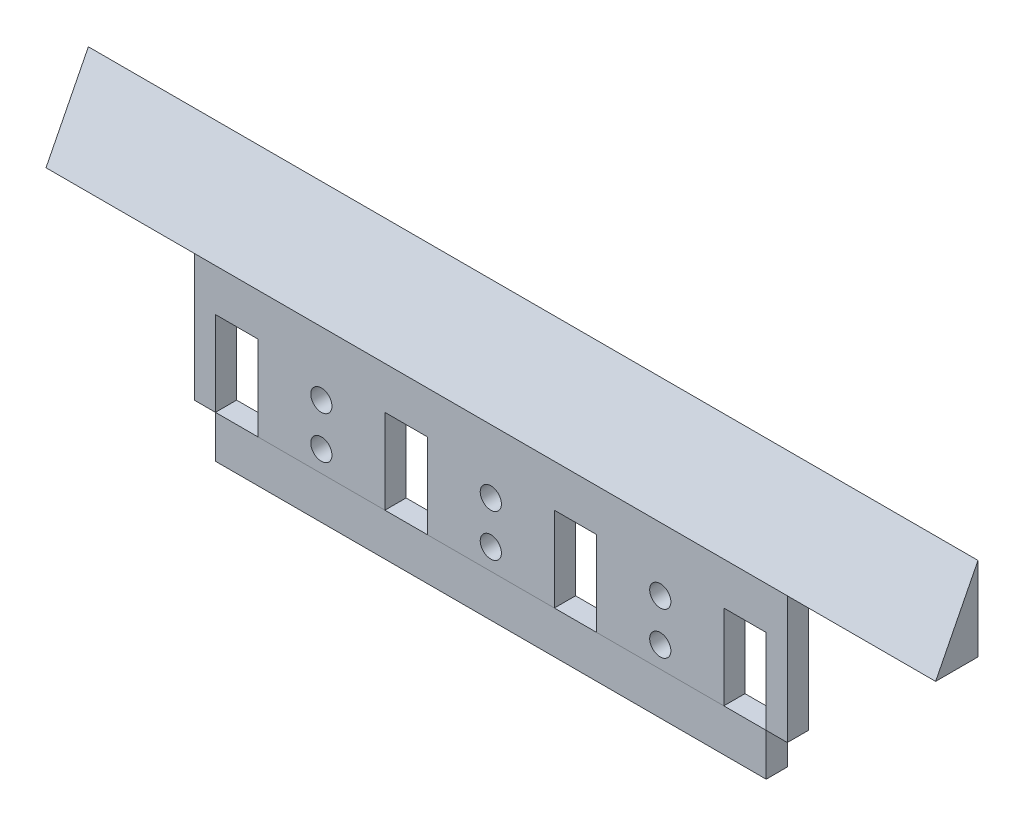
SolidWorks part; units mm, degrees
ref_plane "정면" through (0, 0, 0) normal (0, 0, 1) x (1, 0, 0)
ref_plane "윗면" through (0, 0, 0) normal (0, 1, 0) x (1, 0, 0)
ref_plane "우측면" through (0, 0, 0) normal (1, 0, 0) x (0, 0, -1)
sketch "스케치1" plane through (0, 0, 0) normal (0, 0, 1) x (1, 0, 0)
  line L1 (7863.764, 2335.8779) -> (8003.764, 2335.8779)
  line L2 (7863.764, 2335.8779) -> (7863.764, 2305.8779)
  line L3 (7863.764, 2305.8779) -> (8003.764, 2305.8779)
  line L4 (8003.764, 2335.8779) -> (8003.764, 2305.8779)
  dimension "D1" = 140
  dimension "D2" = 30
extrude "보스-돌출1" add sketch "스케치1" along normal blind 5
sketch "스케치2" plane through (0, 0, 0) normal (0, 0, -1) x (-1, 0, 0)
  line L0 (-7863.764, 2305.8779) -> (-8003.764, 2305.8779) construction
  line L1 (-7998.764, 2325.8779) -> (-7988.764, 2325.8779)
  line L2 (-7998.764, 2325.8779) -> (-7998.764, 2305.8779)
  line L3 (-7998.764, 2305.8779) -> (-7988.764, 2305.8779)
  line L4 (-7988.764, 2325.8779) -> (-7988.764, 2305.8779)
  line L6 (-7958.764, 2325.8779) -> (-7948.764, 2325.8779)
  line L7 (-7958.764, 2325.8779) -> (-7958.764, 2305.8779)
  line L8 (-7958.764, 2305.8779) -> (-7948.764, 2305.8779)
  line L9 (-7948.764, 2325.8779) -> (-7948.764, 2305.8779)
  line L10 (-7918.764, 2325.8779) -> (-7908.764, 2325.8779)
  line L11 (-7918.764, 2325.8779) -> (-7918.764, 2305.8779)
  line L12 (-7918.764, 2305.8779) -> (-7908.764, 2305.8779)
  line L13 (-7908.764, 2325.8779) -> (-7908.764, 2305.8779)
  line L14 (-7878.764, 2325.8779) -> (-7868.764, 2325.8779)
  line L15 (-7878.764, 2325.8779) -> (-7878.764, 2305.8779)
  line L16 (-7878.764, 2305.8779) -> (-7868.764, 2305.8779)
  line L17 (-7868.764, 2325.8779) -> (-7868.764, 2305.8779)
  line L18 (-8003.764, 2305.8779) -> (-8003.764, 2335.8779) construction
  dimension "D1" = 4
  dimension "D2" = 5
  dimension "D3" = 10
  dimension "D4" = 20
extrude "컷-돌출1" cut sketch "스케치2" against normal blind 50
sketch "스케치3" plane through (7863.764, 0, 0) normal (-1, 0, 0) x (0, 0, 1)
  line L0 (0, 2335.8779) -> (-5, 2335.8779)
  line L1 (-5, 2335.8779) -> (-5, 2355.6147)
  line L2 (-5, 2355.6147) -> (20.2, 2305.8779)
  line M4 (5, 2335.8779) -> (0, 2335.8779)
extrude "보스-돌출2" add sketch "스케치3" against normal blind 140 contours L2 L1 L0 M4
sketch "스케치4" plane through (8003.764, 0, 0) normal (1, 0, 0) x (0, 0, -1)
  line L0 (-5, 2335.8779) -> (5, 2335.8779)
  line L1 (5, 2335.8779) -> (5, 2355.6147)
  line L2 (5, 2355.6147) -> (-5, 2335.8779)
extrude "보스-돌출3" add sketch "스케치4" along normal blind 35
sketch "스케치5" plane through (7863.764, 0, 0) normal (-1, 0, 0) x (0, 0, 1)
  line L0 (5, 2335.8779) -> (-5, 2335.8779)
  line L1 (-5, 2335.8779) -> (-5, 2355.6147)
  line L2 (-5, 2355.6147) -> (5, 2335.8779)
extrude "보스-돌출4" add sketch "스케치5" along normal blind 35
sketch "스케치6" plane through (0, 2305.8779, 0) normal (0, -1, 0) x (1, 0, 0)
  line L1 (7868.764, 0) -> (7998.764, 0)
  line L2 (7868.764, 0) -> (7868.764, 5)
  line L3 (7868.764, 5) -> (7998.764, 5)
  line L4 (7998.764, 0) -> (7998.764, 5)
extrude "보스-돌출7" add sketch "스케치6" along normal blind 10 separate body
sketch "스케치7" plane through (0, 0, 5) normal (0, 0, 1) x (1, 0, 0)
  line L0 (7863.764, 2335.8779) -> (8003.764, 2335.8779)
  line L1 (7933.764, 2335.8779) -> (7933.764, 2245.8779)
  line L2 (7933.764, 2245.8779) -> (7923.764, 2263.1984)
  line L3 (7933.764, 2245.8779) -> (7943.764, 2263.1984)
  line L4 (7933.764, 2245.8779) -> (7840.5173, 2407.3859)
  line L5 (7933.764, 2245.8779) -> (8043.2913, 2435.5846)
  line L6 (7890.1037, 2301.4996) -> (7907.4243, 2311.4996)
  line L7 (7890.1037, 2301.4996) -> (7888.6037, 2304.0977)
  line L8 (7907.4243, 2311.4996) -> (7905.9243, 2314.0977)
  line L9 (7888.6037, 2304.0977) -> (7905.9243, 2314.0977)
  line L10 (7977.4243, 2301.4996) -> (7978.9243, 2304.0977)
  line L11 (7978.9243, 2304.0977) -> (7961.6037, 2314.0977)
  line L12 (7977.4243, 2301.4996) -> (7960.1037, 2311.4996)
  line L13 (7960.1037, 2311.4996) -> (7961.6037, 2314.0977)
  circle A0 centre (7933.764, 2245.8779) radius 20
  dimension "D1" = 30
  dimension "D4" = 40
  dimension "D2" = 30
  dimension "D3" = 90
  dimension "D5" = 3
  dimension "D6" = 20
  dimension "D7" = 10
  dimension "D8" = 70
sketch "스케치8" plane through (0, 0, 5) normal (0, 0, 1) x (1, 0, 0)
  line L0 (7878.764, 2325.8779) -> (7908.764, 2325.8779)
  line L1 (7908.764, 2325.8779) -> (7893.764, 2325.8779)
  line L2 (7893.764, 2325.8779) -> (7893.764, 2305.8779)
  line L3 (7878.764, 2305.8779) -> (7908.764, 2305.8779) construction
  line L4 (7958.764, 2325.8779) -> (7988.764, 2325.8779)
  line L5 (7988.764, 2325.8779) -> (7973.764, 2325.8779)
  line L6 (7973.764, 2325.8779) -> (7973.764, 2305.8779)
  line L7 (7958.764, 2305.8779) -> (7988.764, 2305.8779) construction
  line L8 (7918.764, 2325.8779) -> (7948.764, 2325.8779)
  line L9 (7948.764, 2325.8779) -> (7948.764, 2305.8779)
  line L10 (7948.764, 2305.8779) -> (7918.764, 2305.8779)
  line L11 (7918.764, 2305.8779) -> (7918.764, 2325.8779)
  line L12 (7933.764, 2325.8779) -> (7933.764, 2305.8779)
  circle A0 centre (7893.764, 2320.8779) radius 2.5
  circle A1 centre (7893.764, 2310.8779) radius 2.5
  circle A2 centre (7973.764, 2320.8779) radius 2.5
  circle A3 centre (7973.764, 2310.8779) radius 2.5
  circle A4 centre (7933.764, 2320.8779) radius 2.5
  circle A5 centre (7933.764, 2310.8779) radius 2.5
  dimension "D1" = 5
  dimension "D2" = 5
  dimension "D3" = 5
  dimension "D4" = 5
  dimension "D9" = 5
  dimension "D10" = 5
  dimension "D12" = 5
  dimension "D5" = 5
  dimension "D6" = 5
  dimension "D7" = 5
  dimension "D8" = 5
  dimension "D11" = 5
extrude "컷-돌출2" cut sketch "스케치8" against normal blind 10 contours L2 A0 | L2 A0 | L2 A1 | L2 A1 | L12 A4 | L12 A4 | L12 A5 | L12 A5 | L6 A2 | L6 A2 | A3
